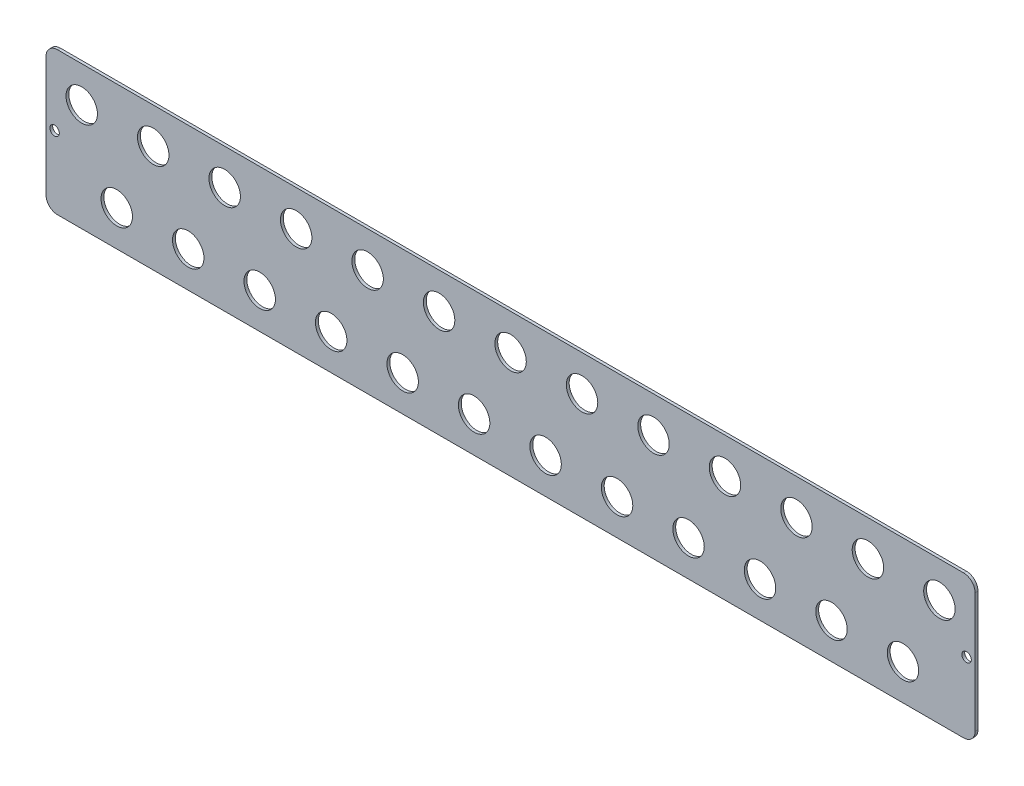
SolidWorks part; units mm, degrees
ref_plane "Front Plane" through (0, 0, 0) normal (0, 0, 1) x (1, 0, 0)
ref_plane "Top Plane" through (0, 0, 0) normal (0, 1, 0) x (1, 0, 0)
ref_plane "Right Plane" through (0, 0, 0) normal (1, 0, 0) x (0, 0, -1)
sketch "Sketch1" plane through (0, 0, 0) normal (0, 0, 1) x (1, 0, 0)
  line L1 (-316.9013, -50) -> (316.9013, -50)
  line L2 (-325, -41.9013) -> (-325, 41.9013)
  line L3 (-316.9013, 50) -> (316.9013, 50)
  line L4 (325, -41.9013) -> (325, 41.9013)
  line L5 (-325, -50) -> (325, 50) construction
  line L6 (-325, 50) -> (325, -50) construction
  arc A0 (316.9013, -50) -> (325, -41.9013) centre (316.9013, -41.9013) ccw
  arc A1 (325, 41.9013) -> (316.9013, 50) centre (316.9013, 41.9013) ccw
  arc A2 (-316.9013, -50) -> (-325, -41.9013) centre (-316.9013, -41.9013) cw
  arc A3 (-325, 41.9013) -> (-316.9013, 50) centre (-316.9013, 41.9013) cw
  point P0 (0, 0)
  dimension "D3" = 8.0987
  dimension "D1" = 100
  dimension "D2" = 650
extrude "Boss-Extrude1" add sketch "Sketch1" along normal blind 2
sketch "Sketch2" plane through (0, 0, 2) normal (0, 0, 1) x (1, 0, 0)
  line L0 (-325, 0) -> (325, 0) construction
  line L1 (-325, 41.9013) -> (-325, -41.9013) construction
  line L2 (325, -41.9013) -> (325, 41.9013) construction
  line L3 (0, 50) -> (0, 0) construction
  line L4 (316.9013, 50) -> (-316.9013, 50) construction
  line L6 (0, 25) -> (325, 25) construction
  circle A0 centre (300, 25) radius 3
  circle A1 centre (-319, 0) radius 3
  circle A2 centre (319, 0) radius 3
  dimension "D1" = 25
  dimension "D2" = 6
  dimension "D3" = 6
  dimension "D4" = 6
  dimension "D5" = 6
  dimension "D6" = 6
extrude "Cut-Extrude2" cut sketch "Sketch2" against normal blind 10
hole_wizard "M20 Clearance Hole2" positions "Sketch6" profile "Sketch5" hole size "M20" standard "ANSI Metric"
sketch "Sketch6" plane through (0, 0, 2) normal (0, 0, 1) x (1, 0, 0)
  point P0 (300, 25)
sketch "Sketch5" plane through (300, 25, 2) normal (1, 0, 0) x (0, -1, 0)
  line L0 (0, 0) -> (0, 12.6095)
  line L1 (0, 12.6095) -> (11, 6)
  line L2 (11, 6) -> (11, 0)
  line L5 (11, 0) -> (0, 0)
  line L10 (0, 12.6095) -> (-11, 6) construction
  line L11 (0, -6.35) -> (0, 107.95) construction
  dimension "Hole Dia." = 22
  dimension "Hole Depth" = 6
  dimension "Drill Angle" = 118
pattern_linear "LPattern1" count 13 spacing 50 along (-1, 0, 0) of "M20 Clearance Hole2"
pattern_linear "LPattern2" count 2 spacing 50 along (0, -1, 0) count 2 spacing 25.5 along (-1, 0, 0) skipping (0, 1), (1, 0) of "M20 Clearance Hole2"
pattern_linear "LPattern3" count 12 spacing 50 along (-1, 0, 0) of "LPattern2"
hole_wizard "M6 Clearance Hole2" positions "Sketch10" profile "Sketch9" hole size "M6" standard "ANSI Metric"
sketch "Sketch10" plane through (0, 0, 0) normal (0, 0, -1) x (-1, 0, 0)
  point P0 (319, 0)
  point P3 (-319, 0)
sketch "Sketch9" plane through (-319, 0, 0) normal (1, 0, 0) x (0, 1, 0)
  line L0 (0, 0) -> (0, 7.9828)
  line L1 (0, 7.9828) -> (3.3, 6)
  line L2 (3.3, 6) -> (3.3, 0)
  line L5 (3.3, 0) -> (0, 0)
  line L10 (0, 7.9828) -> (-3.3, 6) construction
  line L11 (0, -6.35) -> (0, 107.95) construction
  dimension "Hole Dia." = 6.6
  dimension "Hole Depth" = 6
  dimension "Drill Angle" = 118
